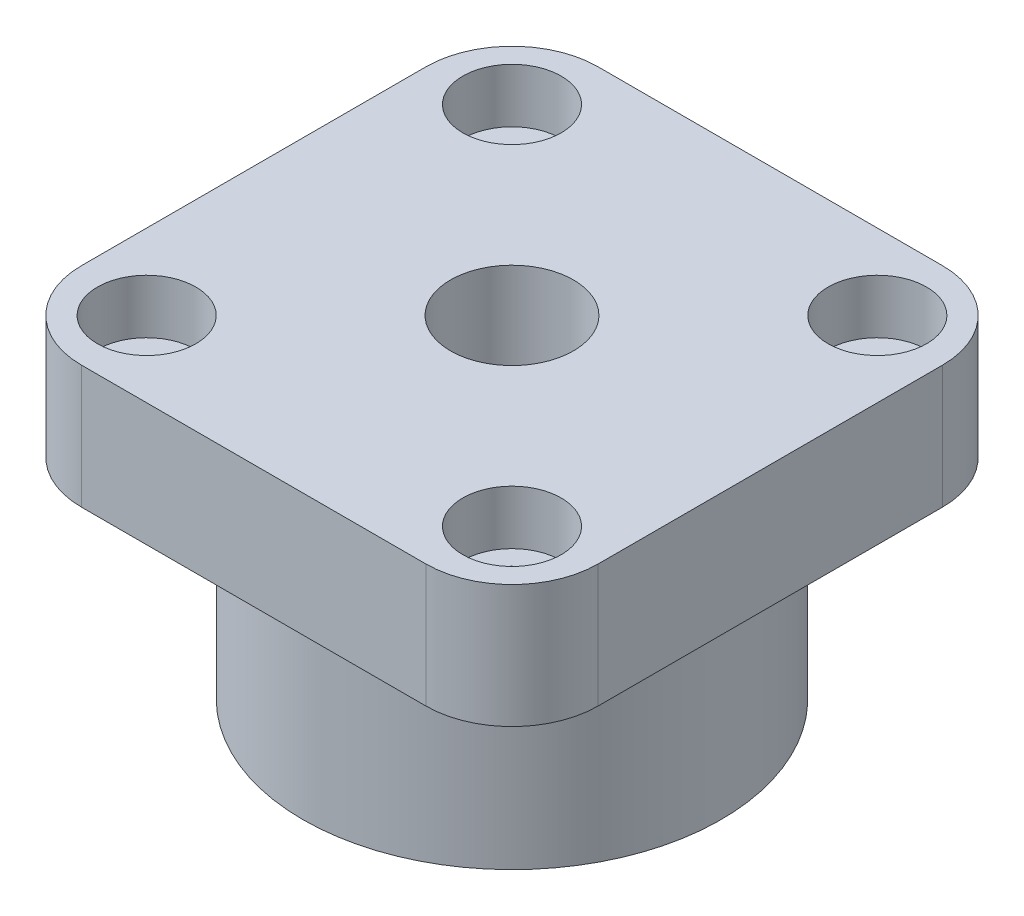
SolidWorks part; units mm, degrees
ref_plane "Front Plane" through (0, 0, 0) normal (0, 0, 1) x (1, 0, 0)
ref_plane "Top Plane" through (0, 0, 0) normal (0, 1, 0) x (1, 0, 0)
ref_plane "Right Plane" through (0, 0, 0) normal (1, 0, 0) x (0, 0, -1)
sketch "Sketch1" plane through (0, 0, 0) normal (0, 1, 0) x (1, 0, 0)
  circle A0 centre (0, 0) radius 17
  circle A1 centre (0, 0) radius 5
  dimension "D1" = 34
  dimension "D2" = 10
extrude "Boss-Extrude1" add sketch "Sketch1" along normal blind 17
sketch "Sketch2" plane through (0, 17, 0) normal (0, 1, 0) x (1, 0, 0)
  line L1 (21, -21) -> (-21, -21)
  line L2 (21, -21) -> (21, 21)
  line L3 (21, 21) -> (-21, 21)
  line L4 (-21, -21) -> (-21, 21)
  line L5 (21, -21) -> (-21, 21) construction
  line L6 (21, 21) -> (-21, -21) construction
  circle A0 centre (0, 0) radius 5
  point P0 (0, 0)
  dimension "D1" = 42
extrude "Boss-Extrude2" add sketch "Sketch2" along normal blind 10
fillet "Fillet1" radius 7 4 edges at (-21, 22, 21) (21, 22, 21) (21, 22, -21) (-21, 22, -21)
sketch "Sketch3" plane through (0, 27, 0) normal (0, 1, 0) x (1, 0, 0)
  line L0 (0, 0) -> (21, 0) construction
  line L1 (21, -14) -> (21, 14) construction
  line L2 (0, 0) -> (0, 21) construction
  line L3 (14, 21) -> (-14, 21) construction
  line L4 (0, 0) -> (22.7556, 22.7556) construction
  point P5 (14.8492, 14.8492)
  point P17 (14.8492, -14.8492)
  point P18 (-14.8492, -14.8492)
  point P19 (-14.8492, 14.8492)
  point P20 (0, 0)
  dimension "D2" = 4
  dimension "D1" = 21
hole_wizard "CBORE for M4 Hex Socket Head Cap Screw1" positions "3DSketch1" profile "Sketch4" counterbore size "M4" standard "ISO" end condition through all
sketch3d "3DSketch1"
  point P0 (-14.8492, 27, -14.8492)
  point P3 (14.8492, 27, -14.8492)
  point P6 (14.8492, 27, 14.8492)
  point P9 (-14.8492, 27, 14.8492)
sketch "Sketch4" plane through (-14.8492, 27, -14.8492) normal (1, 0, 0) x (0, 0, 1)
  line L0 (0, 0) -> (0, 27)
  line L1 (0, 27) -> (2.25, 27)
  line L3 (2.25, 27) -> (2.25, 4.4)
  line L4 (2.25, 4.4) -> (4, 4.4)
  line L5 (4, 4.4) -> (4, 0)
  line L7 (4, 0) -> (0, 0)
  line L11 (0, -6.35) -> (0, 107.95) construction
  dimension "Thru Hole Dia." = 4.5
  dimension "Thru Hole Depth" = 27
  dimension "C'Bore Dia." = 8
  dimension "C'Bore Depth" = 4.4
